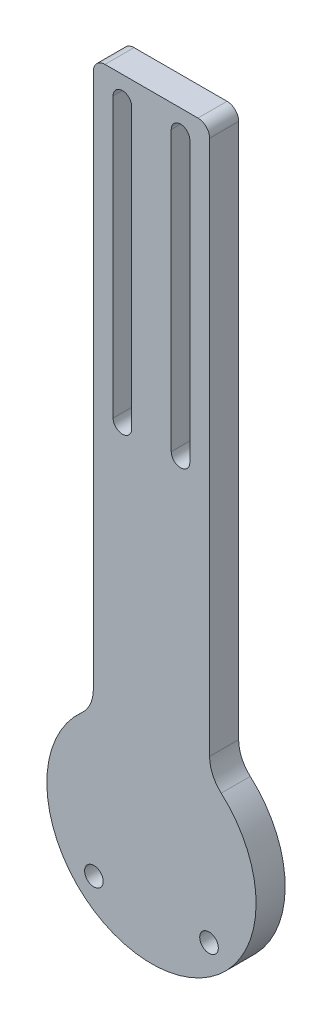
SolidWorks part; units mm, degrees
ref_plane "前视基准面" through (0, 0, 0) normal (0, 0, 1) x (1, 0, 0)
ref_plane "上视基准面" through (0, 0, 0) normal (0, 1, 0) x (1, 0, 0)
ref_plane "右视基准面" through (0, 0, 0) normal (1, 0, 0) x (0, 0, -1)
sketch "草图1" plane through (0, 0, 0) normal (0, 0, 1) x (1, 0, 0)
  line L0 (0, 376.7776) -> (0, -376.7776) construction
  line L1 (-376.7776, 0) -> (376.7776, 0) construction
  line L2 (-9.8995, -9.8995) -> (0, 0) construction
  line L4 (-5, 108) -> (-5, 60) construction
  line L6 (-3.4, 108) -> (-3.4, 60)
  line L7 (-6.6, 108) -> (-6.6, 60)
  line L8 (5, 108) -> (5, 60) construction
  line L9 (3.4, 108) -> (3.4, 60)
  line L10 (6.6, 108) -> (6.6, 60)
  line L11 (-10, 110) -> (-10, 17.8885)
  line L12 (-8, 112) -> (8, 112)
  line L13 (10, 110) -> (10, 17.8885)
  circle A0 centre (0, 0) radius 14 construction
  circle A1 centre (-9.8995, -9.8995) radius 1.6
  circle A2 centre (9.8995, -9.8995) radius 1.6
  arc A5 (-3.4, 108) -> (-6.6, 108) centre (-5, 108) ccw
  arc A6 (-6.6, 60) -> (-3.4, 60) centre (-5, 60) ccw
  arc A7 (3.4, 108) -> (6.6, 108) centre (5, 108) cw
  arc A8 (6.6, 60) -> (3.4, 60) centre (5, 60) cw
  arc A9 (-12, 13.4164) -> (12, 13.4164) centre (0, 0) ccw
  arc A10 (10, 17.8885) -> (12, 13.4164) centre (16, 17.8885) ccw
  arc A11 (-10, 17.8885) -> (-12, 13.4164) centre (-16, 17.8885) cw
  arc A12 (-10, 110) -> (-8, 112) centre (-8, 110) cw
  arc A13 (10, 110) -> (8, 112) centre (8, 110) ccw
  point P13 (-5, 84)
  point P16 (0, 112)
  point P26 (5, 84)
  point P32 (10, 14.9666)
  point P35 (-10, 14.9666)
  point P38 (-10, 112)
  point P41 (10, 112)
  dimension "D1" = 28
  dimension "D3" = 3.2
  dimension "D4" = 36
  dimension "D5" = 20
  dimension "D11" = 6
  dimension "D12" = 2
  dimension "D2" = 45
  dimension "D6" = 112
  dimension "D7" = 3.2
  dimension "D8" = 48
  dimension "D9" = 5
  dimension "D10" = 60
extrude "凸台-拉伸1" add sketch "草图1" along normal blind 5
